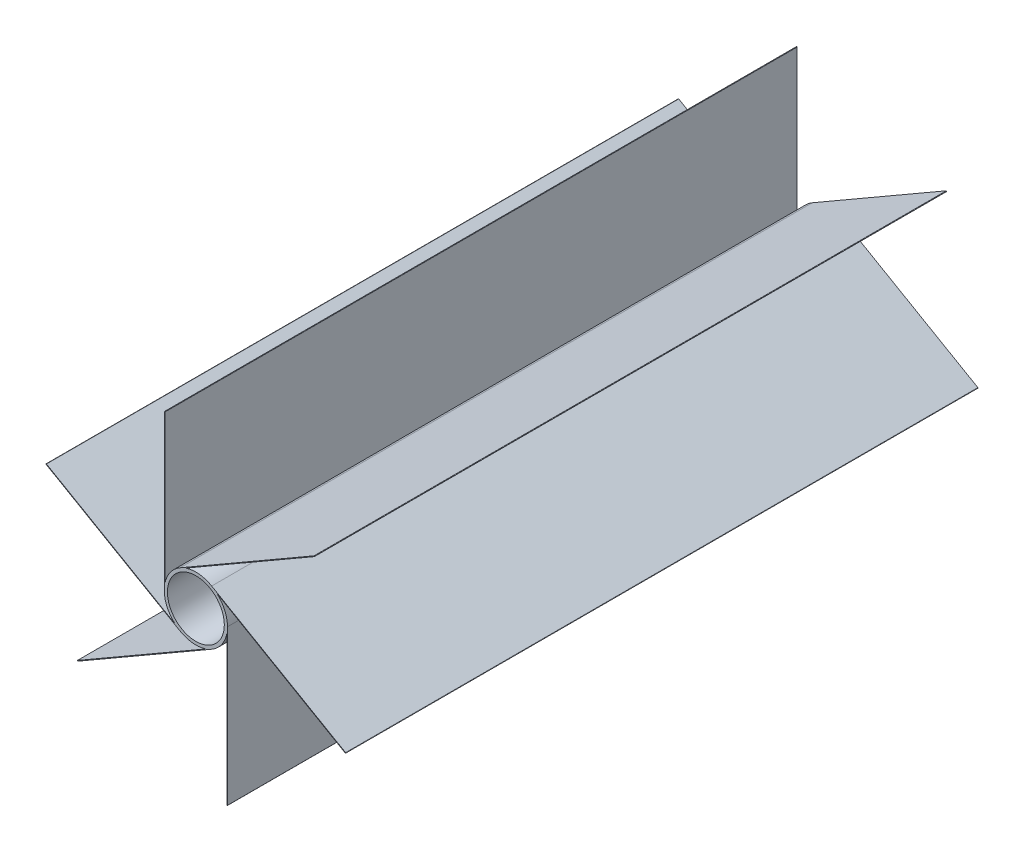
SolidWorks part; units mm, degrees
material "Plain Carbon Steel"
ref_plane "Front Plane" through (0, 0, 0) normal (0, 0, 1) x (1, 0, 0)
ref_plane "Top Plane" through (0, 0, 0) normal (0, 1, 0) x (1, 0, 0)
ref_plane "Right Plane" through (0, 0, 0) normal (1, 0, 0) x (0, 0, -1)
sketch "Sketch2" plane through (0, 0, 0) normal (0, 0, 1) x (1, 0, 0)
  line L0 (-50, 0) -> (-50, 244.5404)
  line L1 (-49, 9.9499) -> (-49, 244.5404)
  line L2 (-25, 43.3013) -> (186.7782, 165.5715)
  line L3 (-15.8832, 47.4102) -> (187.2782, 164.7054)
  line L4 (25, 43.3013) -> (236.7782, -78.9689)
  line L5 (33.1168, 37.4603) -> (236.2782, -79.8349)
  line L6 (50, 0) -> (50, -244.5404)
  line L7 (49, -9.9499) -> (49, -244.5404)
  line L8 (25, -43.3013) -> (-186.7782, -165.5715)
  line L9 (15.8832, -47.4102) -> (-187.2782, -164.7054)
  line L10 (-25, -43.3013) -> (-236.7782, 78.9689)
  line L11 (-33.1168, -37.4603) -> (-236.2782, 79.8349)
  arc A1 (-50, 0) -> (-33.1168, -37.4603) centre (0, 0) ccw
  arc A2 (-49, 244.5404) -> (-50, 244.5404) centre (-49.5, 244.5404) ccw
  arc A3 (187.2782, 164.7054) -> (186.7782, 165.5715) centre (187.0282, 165.1385) ccw
  arc A4 (236.2782, -79.8349) -> (236.7782, -78.9689) centre (236.5282, -79.4019) ccw
  arc A5 (49, -244.5404) -> (50, -244.5404) centre (49.5, -244.5404) ccw
  arc A6 (-187.2782, -164.7054) -> (-186.7782, -165.5715) centre (-187.0282, -165.1385) ccw
  arc A7 (-236.2782, 79.8349) -> (-236.7782, 78.9689) centre (-236.5282, 79.4019) ccw
  arc A8 (-25, -43.3013) -> (15.8832, -47.4102) centre (0, 0) ccw
  arc A9 (25, -43.3013) -> (49, -9.9499) centre (0, 0) ccw
  arc A10 (50, 0) -> (33.1168, 37.4603) centre (0, 0) ccw
  arc A11 (25, 43.3013) -> (-15.8832, 47.4102) centre (0, 0) ccw
  arc A12 (-25, 43.3013) -> (-49, 9.9499) centre (0, 0) ccw
  circle A13 centre (0, 0) radius 250 construction
  circle A14 centre (0, 0) radius 45
  point P36 (0, 0)
  dimension "D1" = 100
  dimension "D2" = 6
  dimension "D3" = 1
extrude "Boss-Extrude1" add sketch "Sketch2" along normal blind 1000
sketch "Sketch3" plane through (0, 0, 0) normal (0, 0, -1) x (-1, 0, 0)
  circle A0 centre (0, 0) radius 12.5
extrude "Boss-Extrude2" add sketch "Sketch3" along normal blind 27
sketch "Sketch4" plane through (0, 0, -27) normal (0, 0, -1) x (-1, 0, 0)
  circle A0 centre (0, 0) radius 10
extrude "Boss-Extrude3" add sketch "Sketch4" along normal blind 48
thread "Thread1" pitch 1.5 start angle 0, offset 0, length 33, pitch 1.5, diameter 20
ref_plane "Plane1" through (10, 0, -75) normal (0, -1, 0) x (1, 0, 0)
sketch "Thread Profile1" plane through (10, 0, -75) normal (0, -1, 0) x (1, 0, 0)
  line L0 (0, 0) -> (0, 1.5) construction
  line L11 (0, 0) -> (0, 1.3125)
  line L12 (0, 1.3125) -> (-0.8119, 0.8437)
  line L13 (-0.8119, 0.8437) -> (-0.8119, 0.4687)
  line L15 (-0.8119, 0.4687) -> (0, 0)
  line L17 (-0.8119, 0.6562) -> (0, 0.6562) construction
  point P2 (0, 0)
  dimension "Pitch" = 1.5
  dimension "Profile_Angle" = 60
  dimension "Profile_Land" = 0.375
  dimension "Profile_Height" = 0.8119
ref_plane "Plane2" through (0, 0, 500) normal (0, 0, 1) x (1, 0, 0)
sketch "Sketch12" plane through (0, 0, 0) normal (0, 0, -1) x (-1, 0, 0)
  circle A12 centre (0, 0) radius 45
extrude "Boss-Extrude4" add sketch "Sketch12" against normal blind 10
